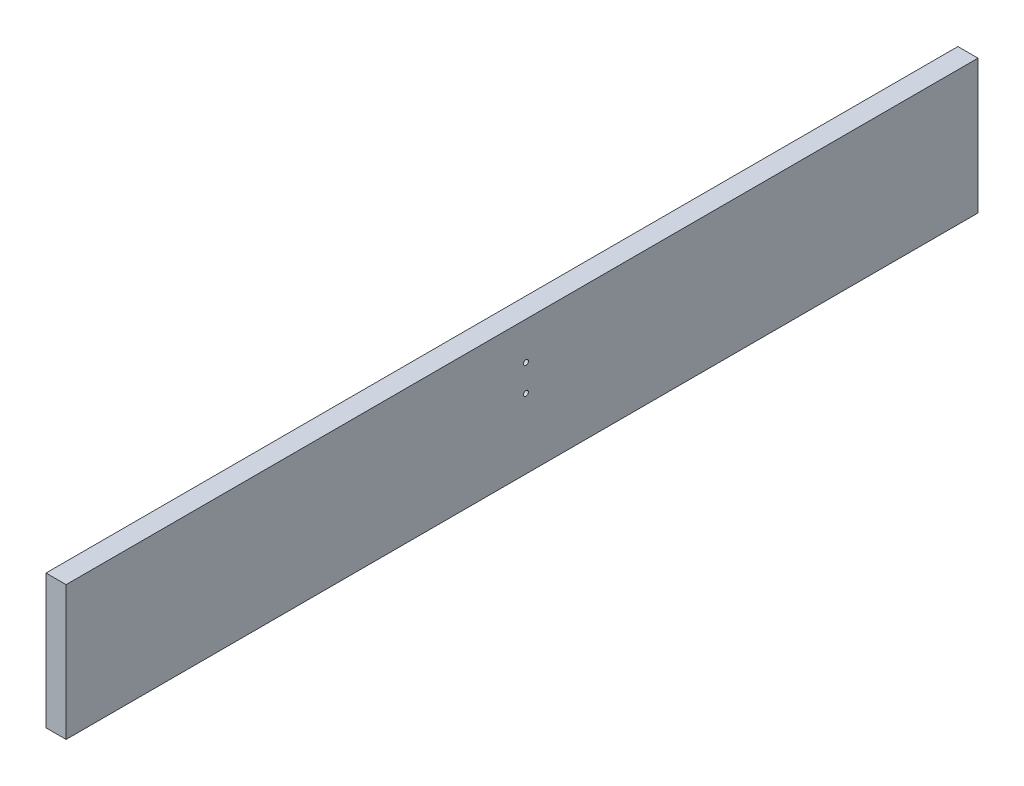
SolidWorks part; units mm, degrees
ref_plane "Front Plane" through (0, 0, 0) normal (0, 0, 1) x (1, 0, 0)
ref_plane "Top Plane" through (0, 0, 0) normal (0, 1, 0) x (1, 0, 0)
ref_plane "Right Plane" through (0, 0, 0) normal (1, 0, 0) x (0, 0, -1)
sketch "Sketch1" plane through (0, 0, 0) normal (0, 0, 1) x (1, 0, 0)
  line L1 (-9.525, 63.5) -> (9.525, 63.5)
  line L2 (-9.525, 63.5) -> (-9.525, -63.5)
  line L3 (-9.525, -63.5) -> (9.525, -63.5)
  line L4 (9.525, 63.5) -> (9.525, -63.5)
  line L5 (-9.525, 63.5) -> (9.525, -63.5) construction
  line L6 (-9.525, -63.5) -> (9.525, 63.5) construction
  point P0 (0, 0)
  dimension "D1" = 127
  dimension "D2" = 19.05
extrude "Boss-Extrude1" add sketch "Sketch1" along normal blind 863.6
sketch "Sketch2" plane through (-9.525, 0, 0) normal (-1, 0, 0) x (0, 0, 1)
  circle A0 centre (428.1396, 2.54) radius 2.3813
  circle A1 centre (428.1396, 27.94) radius 2.3813
extrude "Cut-Extrude1" cut sketch "Sketch2" against normal through all
